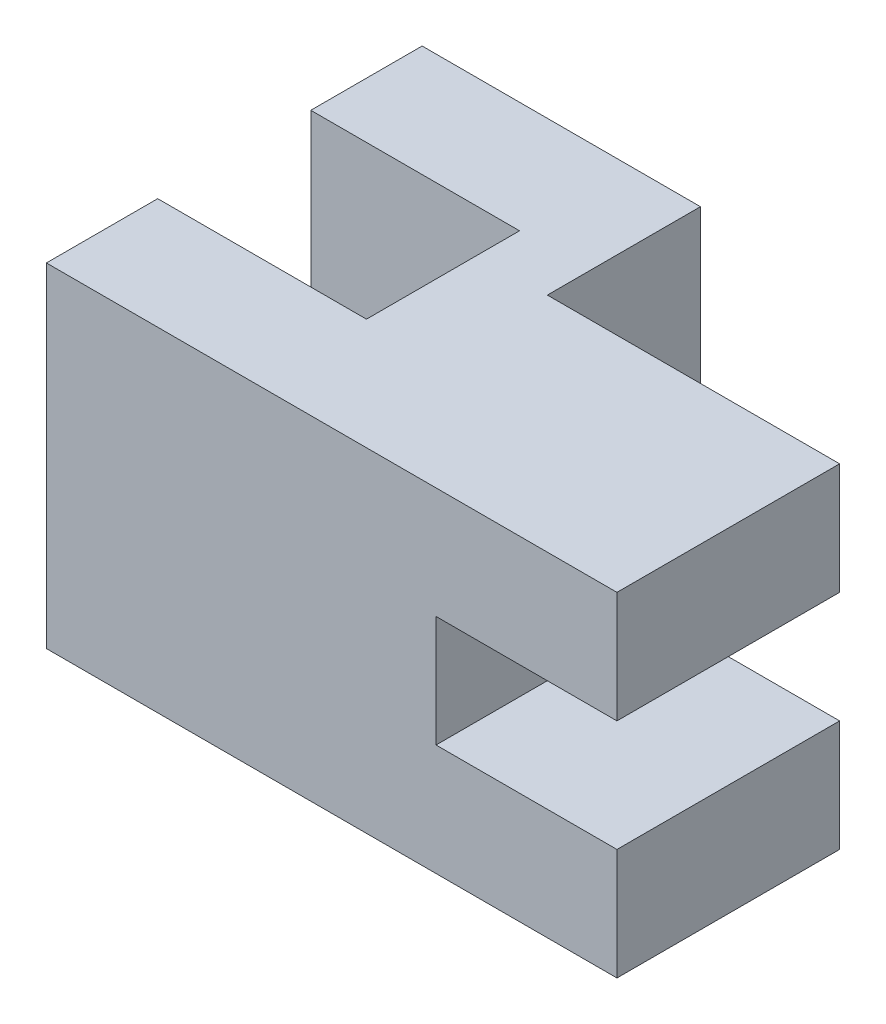
SolidWorks part; units mm, degrees
ref_plane "前视基准面" through (0, 0, 0) normal (0, 0, 1) x (1, 0, 0)
ref_plane "上视基准面" through (0, 0, 0) normal (0, 1, 0) x (1, 0, 0)
ref_plane "右视基准面" through (0, 0, 0) normal (1, 0, 0) x (0, 0, -1)
other "Configuration Table"
sketch "草图1" plane through (0, 0, 0) normal (0, 1, 0) x (1, 0, 0)
  line L0 (0, 11) -> (0, 0)
  line L1 (-15, 19) -> (5, 19)
  line L2 (-15, 19) -> (-15, 11)
  line L3 (-15, 11) -> (0, 11)
  line L9 (0, 0) -> (-15, 0)
  line L12 (-15, 0) -> (-15, -8)
  line L15 (5, 8) -> (26, 8)
  line L16 (26, -8) -> (26, 8)
  line L17 (5, 19) -> (5, 8)
  line L18 (-15, -8) -> (26, -8)
  line L19 (13, -1000.9497) -> (13, 48999.0503) construction
  dimension "D1" = 20
  dimension "D2" = 8
  dimension "D3" = 8
  dimension "D4" = 27
  dimension "D5" = 16
  dimension "D6" = 41
  dimension "D7" = 13
extrude "凸台-拉伸1" add sketch "草图1" along normal mid plane 24
sketch "草图2" plane through (0, 0, 8) normal (0, 0, 1) x (1, 0, 0)
  line L0 (-1000, 0) -> (49000, 0) construction
  line L1 (26, 12) -> (26, -12) construction
  line L2 (13, -4) -> (26, -4)
  line L3 (13, -4) -> (13, 4)
  line L4 (13, 4) -> (26, 4)
  line L5 (26, -4) -> (26, 4)
  line L6 (13, -4) -> (26, 4) construction
  line L7 (13, 4) -> (26, -4) construction
  point P1 (19.5, 0)
  dimension "D1" = 8
  dimension "D2" = 13
extrude "切除-拉伸1" cut sketch "草图2" against normal blind 24
